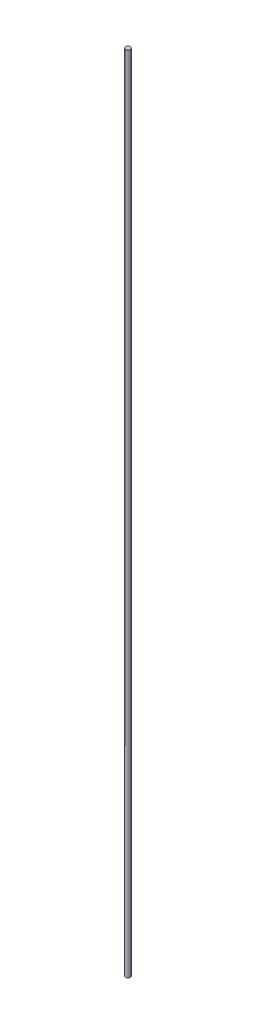
SolidWorks part; units mm, degrees
material "Медь"
ref_plane "Спереди" through (0, 0, 0) normal (0, 0, 1) x (1, 0, 0)
ref_plane "Сверху" through (0, 0, 0) normal (0, 1, 0) x (1, 0, 0)
ref_plane "Справа" through (0, 0, 0) normal (1, 0, 0) x (0, 0, -1)
sketch "Эскиз1" plane through (0, 0, 0) normal (0, 1, 0) x (1, 0, 0)
  circle A0 centre (0, 0) radius 1.5
  dimension "D1" = 3
extrude "Бобышка-Вытянуть1" add sketch "Эскиз1" along normal blind 500
